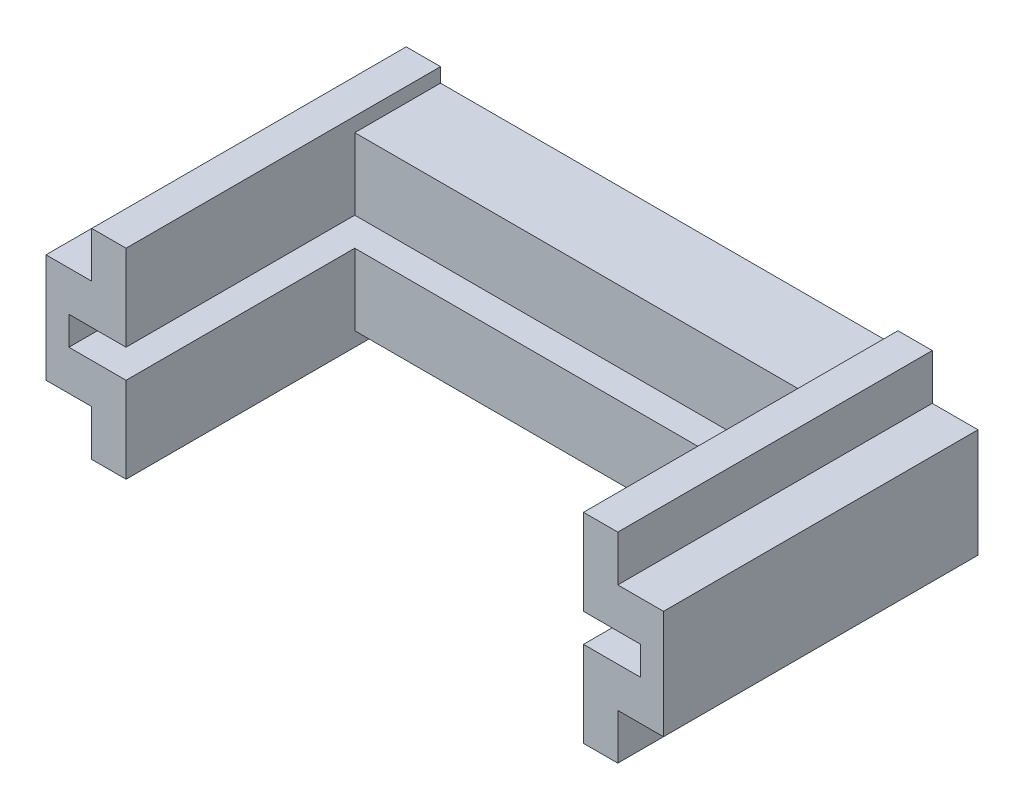
SolidWorks part; units mm, degrees
ref_plane "Front Plane" through (0, 0, 0) normal (0, 0, 1) x (1, 0, 0)
ref_plane "Top Plane" through (0, 0, 0) normal (0, 1, 0) x (1, 0, 0)
ref_plane "Right Plane" through (0, 0, 0) normal (1, 0, 0) x (0, 0, -1)
sketch "Sketch1" plane through (0, 0, 0) normal (0, 0, 1) x (1, 0, 0)
  line L1 (-29.21, -11.1125) -> (29.21, -11.1125)
  line L2 (-34.29, -6.0325) -> (-34.29, 6.0325)
  line L3 (-29.21, 11.1125) -> (29.21, 11.1125)
  line L4 (34.29, -6.0325) -> (34.29, 6.0325)
  line L9 (-34.29, 6.0325) -> (-29.21, 6.0325)
  line L10 (-29.21, 11.1125) -> (-29.21, 6.0325)
  line L13 (-34.29, -6.0325) -> (-29.21, -6.0325)
  line L14 (-29.21, -11.1125) -> (-29.21, -6.0325)
  line L17 (34.29, -6.0325) -> (29.21, -6.0325)
  line L18 (29.21, -11.1125) -> (29.21, -6.0325)
  line L21 (34.29, 6.0325) -> (29.21, 6.0325)
  line L22 (29.21, 11.1125) -> (29.21, 6.0325)
  point P0 (0, 0)
  point P1 (0, 0)
  point P2 (0, 11.1125)
  point P3 (0, 0)
  point P4 (-34.29, 0)
  point P18 (-53.7979, -27.4266)
  dimension "D1" = 68.58
  dimension "D2" = 22.225
  dimension "D3" = 5.08
extrude "Boss-Extrude1" add sketch "Sketch1" along normal blind 9.525
sketch "Sketch3" plane through (0, 0, 9.525) normal (0, 0, 1) x (1, 0, 0)
  line L0 (29.21, 11.1125) -> (-29.21, 11.1125) construction
  line L1 (-29.21, 11.1125) -> (-25.4, 11.1125)
  line L2 (-34.29, 6.0325) -> (-34.29, -6.0325)
  line L3 (-29.21, -11.1125) -> (-25.4, -11.1125)
  line L4 (-25.4, 11.1125) -> (-25.4, 1.5875)
  line L5 (-29.21, -11.1125) -> (29.21, -11.1125) construction
  line L6 (0, 0) -> (0, 11.1125) construction
  line L7 (-25.4, 1.5875) -> (-31.75, 1.5875)
  line L9 (-25.4, -1.5875) -> (-31.75, -1.5875)
  line L10 (-31.75, 1.5875) -> (-31.75, -1.5875)
  line L11 (-25.4, -1.5875) -> (-25.4, -11.1125)
  line L12 (25.4, -1.5875) -> (25.4, -11.1125)
  line L13 (31.75, 1.5875) -> (31.75, -1.5875)
  line L14 (25.4, -1.5875) -> (31.75, -1.5875)
  line L15 (25.4, 1.5875) -> (31.75, 1.5875)
  line L16 (25.4, 11.1125) -> (25.4, 1.5875)
  line L17 (29.21, -11.1125) -> (25.4, -11.1125)
  line L18 (34.29, 6.0325) -> (34.29, -6.0325)
  line L19 (29.21, 11.1125) -> (25.4, 11.1125)
  line L20 (-34.29, 6.0325) -> (-34.29, -6.0325) construction
  line L21 (29.21, -11.1125) -> (29.21, -6.0325) construction
  line L24 (-34.29, 6.0325) -> (-29.21, 6.0325)
  line L25 (-29.21, 11.1125) -> (-29.21, 6.0325)
  line L26 (-29.21, -6.0325) -> (-34.29, -6.0325)
  line L27 (-29.21, -6.0325) -> (-29.21, -11.1125)
  line L32 (34.29, -6.0325) -> (29.21, -6.0325)
  line L33 (29.21, -11.1125) -> (29.21, -6.0325)
  line L34 (29.21, -6.0325) -> (34.29, -6.0325) construction
  line L37 (34.29, 6.0325) -> (29.21, 6.0325)
  line L38 (29.21, 11.1125) -> (29.21, 6.0325)
  line L39 (34.29, -6.0325) -> (34.29, 6.0325) construction
  point P12 (-31.75, 0)
  point P43 (29.21, 8.3912)
  dimension "D1" = 6.35
  dimension "D2" = 3.175
  dimension "D4" = 25.4
extrude "Boss-Extrude2" add sketch "Sketch3" along normal blind 25.4
sketch "Sketch4" plane through (0, 0, 9.525) normal (0, 0, 1) x (1, 0, 0)
  line L1 (-31.75, -1.5875) -> (31.75, -1.5875)
  line L2 (-31.75, -1.5875) -> (-31.75, 1.5875)
  line L3 (-31.75, 1.5875) -> (31.75, 1.5875)
  line L4 (31.75, -1.5875) -> (31.75, 1.5875)
extrude "Cut-Extrude1" cut sketch "Sketch4" against normal blind 6.35
sketch "Sketch5" plane through (0, 0, 9.525) normal (0, 0, 1) x (1, 0, 0)
  line L0 (25.4, 11.1125) -> (-25.4, 11.1125) construction
  line L1 (-25.4, 11.1125) -> (25.4, 11.1125)
  line L2 (-25.4, 11.1125) -> (-25.4, 9.525)
  line L3 (-25.4, 9.525) -> (25.4, 9.525)
  line L4 (25.4, 11.1125) -> (25.4, 9.525)
  line L5 (0, 0) -> (12.7, 0) construction
  line L6 (25.4, -11.1125) -> (25.4, -9.525)
  line L7 (-25.4, -9.525) -> (25.4, -9.525)
  line L8 (-25.4, -11.1125) -> (-25.4, -9.525)
  line L9 (-25.4, -11.1125) -> (25.4, -11.1125)
  line L10 (-25.4, 1.5875) -> (-25.4, 11.1125) construction
  point P6 (0, 9.525)
  point P14 (0, 0)
  dimension "D1" = 1.5875
extrude "Cut-Extrude2" cut sketch "Sketch5" against normal through all both and the other way through all
